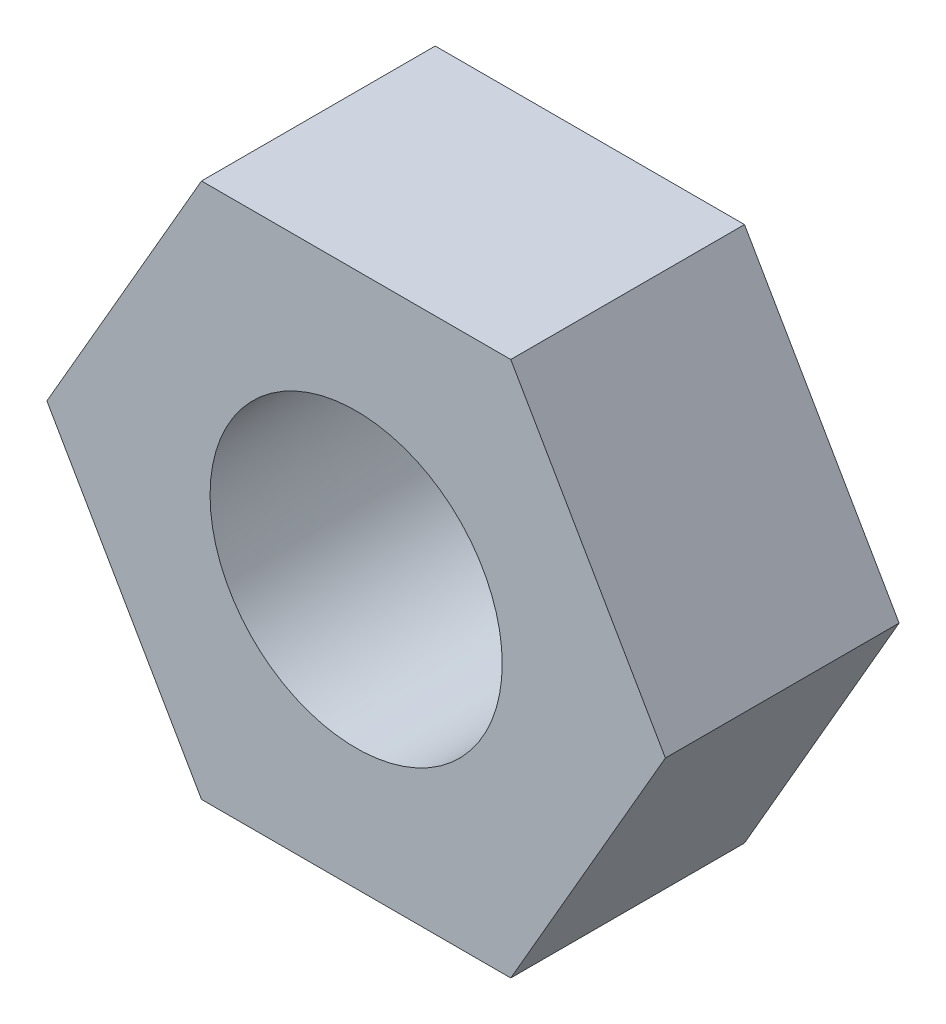
SolidWorks part; units mm, degrees
ref_plane "Plan de face" through (0, 0, 0) normal (0, 0, 1) x (1, 0, 0)
ref_plane "Plan de dessus" through (0, 0, 0) normal (0, 1, 0) x (1, 0, 0)
ref_plane "Plan de droite" through (0, 0, 0) normal (1, 0, 0) x (0, 0, -1)
sketch "Esquisse1" plane through (0, 0, 0) normal (0, 0, 1) x (1, 0, 0)
  line L1 (3.1754, 0) -> (1.5877, 2.75)
  line L2 (1.5877, 2.75) -> (-1.5877, 2.75)
  line L3 (-1.5877, 2.75) -> (-3.1754, 0)
  line L4 (-3.1754, 0) -> (-1.5877, -2.75)
  line L5 (-1.5877, -2.75) -> (1.5877, -2.75)
  line L6 (1.5877, -2.75) -> (3.1754, 0)
  circle A0 centre (0, 0) radius 1.5
  circle A1 centre (0, 0) radius 2.75 construction
  dimension "D1" = 3
  dimension "D2" = 5.5
extrude "Boss.-Extru.1" add sketch "Esquisse1" along normal blind 2.4
